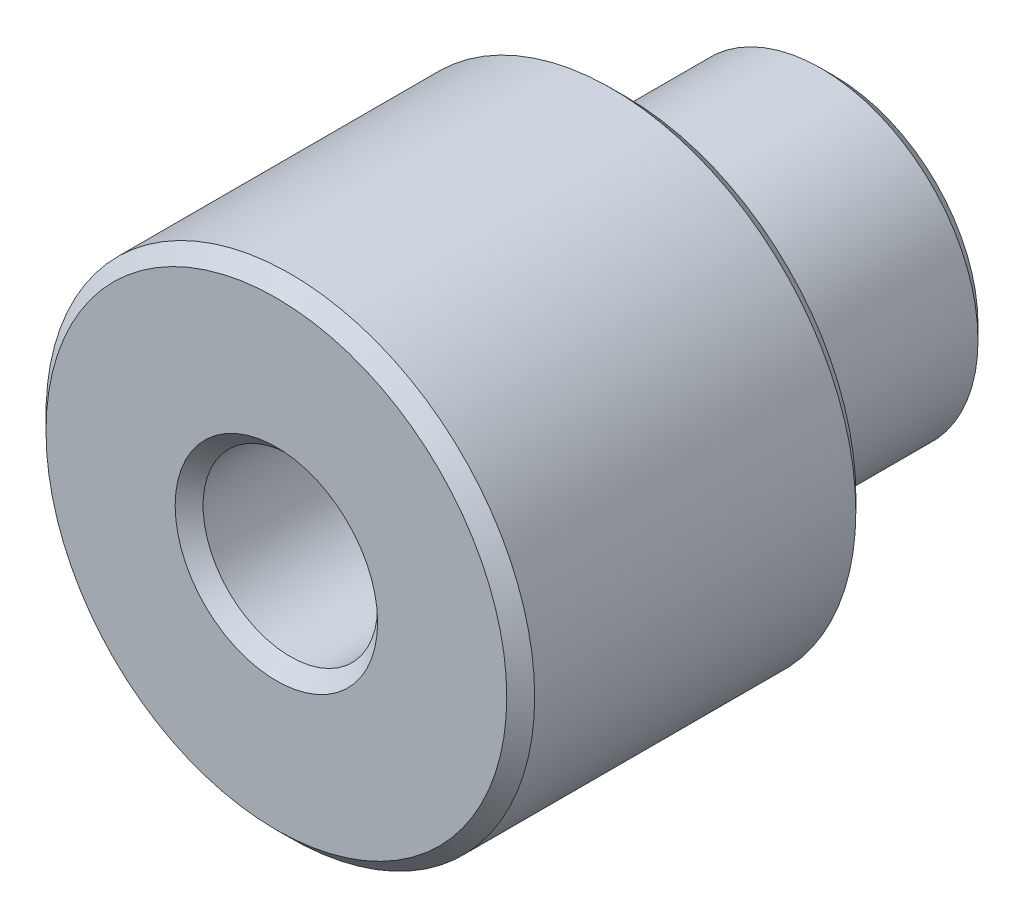
SolidWorks part; units mm, degrees
ref_plane "Спереди" through (0, 0, 0) normal (0, 0, 1) x (1, 0, 0)
ref_plane "Сверху" through (0, 0, 0) normal (0, 1, 0) x (1, 0, 0)
ref_plane "Справа" through (0, 0, 0) normal (1, 0, 0) x (0, 0, -1)
sketch "Эскиз1" plane through (0, 0, 0) normal (0, 0, 1) x (1, 0, 0)
  circle A0 centre (0, 0) radius 3.5
  dimension "D1" = 7
extrude "Бобышка-Вытянуть1" add sketch "Эскиз1" along normal blind 5
sketch "Эскиз2" plane through (0, 0, 0) normal (0, 0, -1) x (-1, 0, 0)
  circle A0 centre (0, 0) radius 2.25
  dimension "D1" = 4.5
extrude "Бобышка-Вытянуть2" add sketch "Эскиз2" along normal blind 3
chamfer "Фаска1" distance 0.2 angle 45 3 edges at (-2.25, 0, -3) (3.5, 0, 0) (3.5, 0, 5)
sketch "Эскиз4" plane through (0, 0, 5) normal (0, 0, 1) x (1, 0, 0)
  circle A0 centre (0, 0) radius 1.25
  dimension "D1" = 2.5
extrude "Вырез-Вытянуть1" cut sketch "Эскиз4" against normal blind 9
chamfer "Фаска2" distance 0.2 angle 45 2 edges at (-1.25, 0, -3) (1.25, 0, 5)
